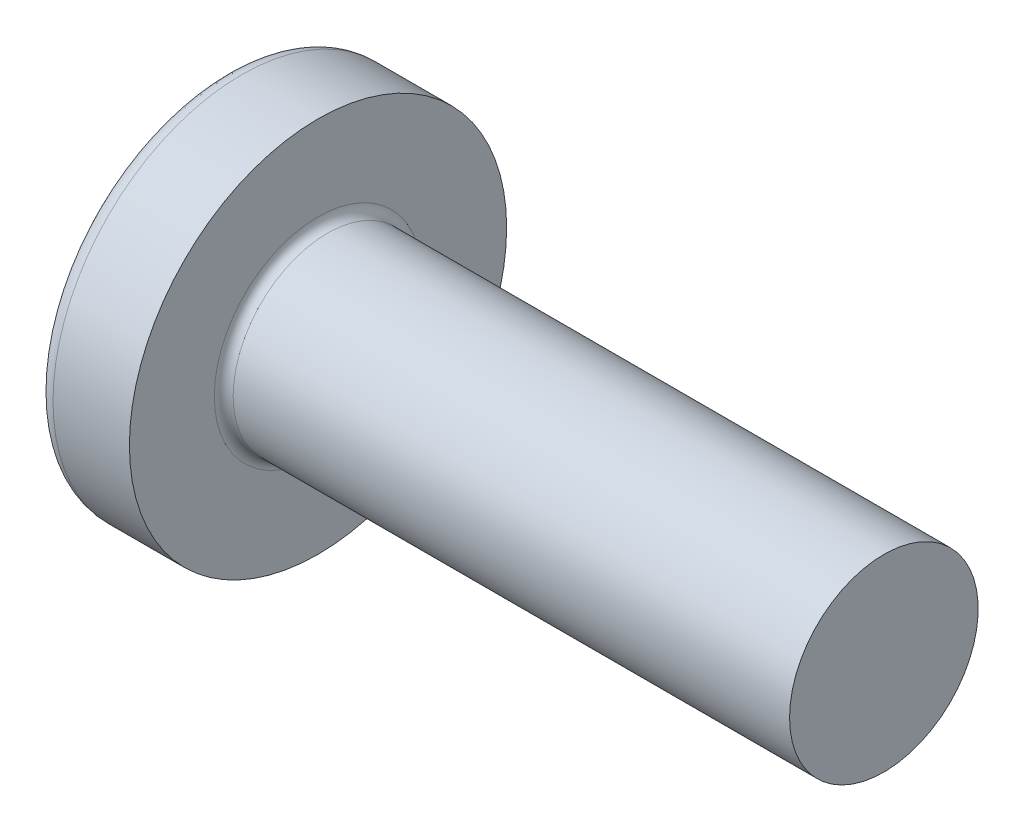
SolidWorks part; units mm, degrees
ref_plane "Plane1" through (0, 0, 0) normal (0, 0, 1) x (1, 0, 0)
ref_plane "Plane2" through (0, 0, 0) normal (0, 1, 0) x (1, 0, 0)
ref_plane "Plane3" through (0, 0, 0) normal (1, 0, 0) x (0, 0, -1)
sketch "BodySke" plane through (0, 0, 0) normal (0, 0, 1) x (1, 0, 0)
  line L0 (1.6, 1) -> (1.6, 2)
  line L1 (1.8, 6.35) -> (1.8, -3.175) construction
  line L2 (-25.4, 0) -> (127, 0) construction
  line L3 (7.6, 0) -> (0, 0)
  line L4 (1.6, 1) -> (7.6, 1)
  line L5 (7.6, 1) -> (7.6, 0)
  line L6 (0.79, 2) -> (1.6, 2)
  line L8 (1.6, 6.35) -> (1.6, -3.175) construction
  arc A0 (0.6464, 1.9285) -> (0, 0) centre (3.2, 0) ccw
  arc A2 (0.6464, 1.9285) -> (0.79, 2) centre (0.79, 1.82) cw
  dimension "Head_crown_rad" = 3.2
  dimension "Head_fillet_rad" = 0.18
  dimension "Length" = 6
  dimension "Head_ht" = 1.6
  dimension "Head_dia" = 4
  dimension "Advance" = 0.4
  dimension "Thread_nom" = 6
  dimension "Diameter" = 2
revolve "Base-Revolve" add sketch "BodySke"
cosmetic thread "ThreadCosmetic" [suppressed]
fillet "Fillet1" radius 0.1 1 edges at (1.6, 0, 1)
sketch "Sketch3" plane through (0, 0, 0) normal (1, 0, 0) x (0, 0, -1)
  line L0 (0.24, -1.05) -> (-0.24, -1.05)
  line L1 (0.24, -1.05) -> (0.24, 1.05)
  line L2 (-0.24, 1.05) -> (0.24, 1.05)
  line L3 (-0.24, 1.05) -> (-0.24, -1.05)
  dimension "Cross_dia" = 2.1
  dimension "D1" = 1.05
  dimension "Cross_width" = 0.48
  dimension "D2" = 0.24
ref_plane "Plane4" through (1.42, 0, 0) normal (1, 0, 0) x (0, 0, -1)
sketch "Sketch4" plane through (1.42, 0, 0) normal (1, 0, 0) x (0, 0, -1)
  line L0 (0.24, -0.342) -> (-0.24, -0.342)
  line L1 (0.24, -0.342) -> (0.24, 0.342)
  line L2 (-0.24, 0.342) -> (0.24, 0.342)
  line L3 (-0.24, 0.342) -> (-0.24, -0.342)
  dimension "D1" = 0.48
  dimension "D2" = 0.684
  dimension "D3" = 0.24
  dimension "D4" = 0.342
loft "Recess" cut profiles "Sketch3", "Sketch4"
pattern_circular "RecPat" count 2 every 90 about axis through (0, 0, 0) along (1, 0, 0) of "Recess"
sketch "RecCorSke" plane through (0, 0, 0) normal (0, 0, 1) x (1, 0, 0)
  line L0 (-3.175, 0) -> (15.875, 0) construction
  line L1 (-25.4, 0) -> (127, 0) construction
  line L2 (0, 0) -> (0, 0.4548)
  line L3 (0, 0.4548) -> (1.42, 0.3555)
  line L4 (1.42, 0.3555) -> (1.5355, 0)
  line L5 (1.5355, 0) -> (0, 0)
  dimension "Diameter" = 0.711
  dimension "Depth" = 1.42
  dimension "Draft_angle" = 4
  dimension "Bottom_angle" = 18
revolve "RecessCore" cut sketch "RecCorSke" angle 360 about L0
sketch "ThdSchSke" plane through (0, 0, 0) normal (0, 0, 1) x (1, 0, 0)
  line L0 (2.4, -0.774) -> (2.2418, -1)
  line L1 (2.4, -0.774) -> (2.5582, -1)
  line L2 (2.5582, -1) -> (2.5582, -1.25)
  line L3 (-3.175, 0) -> (5.1513, 0) construction
  line L5 (2.5582, -1.25) -> (2.2418, -1.25)
  line L6 (2.2418, -1.25) -> (2.2418, -1)
  dimension "Diameter" = 2
  dimension "SideAngle" = 55
  dimension "VeeAngle" = 70
  dimension "Thread_minor" = 1.548
  dimension "Overcut" = 2.5
  dimension "Start" = 2.4
revolve "ThreadSchematic" [suppressed] cut sketch "ThdSchSke" angle 360 about L3
pattern_linear "ThdSchPat" [suppressed]
equation "\"D1@Sketch3\" = \"Cross_dia@Sketch3\" / 2"
equation "\"D2@Sketch3\" = \"Cross_width@Sketch3\" / 2"
equation "\"Depth@RecCorSke\" = \"Cross_depth@Plane4\""
equation "\"D1@Sketch4\" = \"Cross_width@Sketch3\""
equation "\"D2@Sketch4\" = \"Cross_dia@Sketch3\" - 2.0 * \"Cross_depth@Plane4\" * tan(26.5  * 0.017453292)"
equation "\"D3@Sketch4\" = \"D1@Sketch4\" / 2"
equation "\"D4@Sketch4\" = \"D2@Sketch4\" / 2"
equation "\"Thread_length@ThreadCosmetic\" = ((sgn( (\"Length@BodySke\" - \"Advance@BodySke\" * 2.0 ) - \"Thread_nom@BodySke\" )-1)*( (\"Length@BodySke\" - \"Advance@BodySke\" * 2.0 ) - \"Thread_nom@BodySke\" ))/-2+ \"Thread_nom@BodySke\""
equation "\"Thread_minor@ThdSchSke\" = \"Thread_minor@ThreadCosmetic\""
equation "\"Diameter@ThdSchSke\" = \"Diameter@BodySke\""
equation "\"Overcut@ThdSchSke\" = \"Diameter@BodySke\" * 1.25"
equation "\"Start@ThdSchSke\" = \"Head_ht@BodySke\" + \"Length@BodySke\" - \"Thread_length@ThreadCosmetic\"  '---Non-countersunk---"
equation "\"Num_threads@ThdSchPat\" = int( \"Thread_length@ThreadCosmetic\" / \"Advance@BodySke\" + 0.999 )  + 1"
equation "\"Advance@ThdSchPat\" = \"Thread_length@ThreadCosmetic\" /  (\"Num_threads@ThdSchPat\" - 1) 'relax it"
